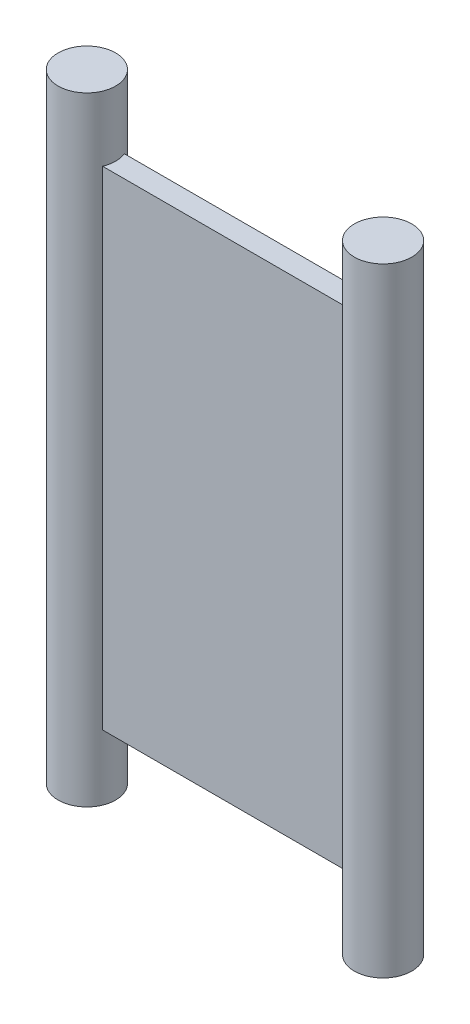
SolidWorks part; units mm, degrees
ref_plane "Front Plane" through (0, 0, 0) normal (0, 0, 1) x (1, 0, 0)
ref_plane "Top Plane" through (0, 0, 0) normal (0, 1, 0) x (1, 0, 0)
ref_plane "Right Plane" through (0, 0, 0) normal (1, 0, 0) x (0, 0, -1)
sketch "Sketch1" plane through (0, 0, 0) normal (0, 1, 0) x (1, 0, 0)
  line L1 (6.826, 0.5) -> (-6.826, 0.5)
  line L2 (6.826, 0.5) -> (6.826, -0.5)
  line L3 (6.826, -0.5) -> (-6.826, -0.5)
  line L4 (-6.826, 0.5) -> (-6.826, -0.5)
  line L5 (6.826, 0.5) -> (-6.826, -0.5) construction
  line L6 (6.826, -0.5) -> (-6.826, 0.5) construction
  point P0 (0, 0)
  dimension "D1" = 13.652
  dimension "D3" = 1
extrude "Boss-Extrude1" add sketch "Sketch1" along normal blind 22.5
ref_plane "Plane1" through (0, 11.25, 0) normal (0, 1, 0) x (1, 0, 0)
sketch "Sketch2" plane through (0, 11.25, 0) normal (0, 1, 0) x (1, 0, 0)
  line L0 (6.826, -0.5) -> (6.826, 0.5) construction
  line L1 (-6.826, 0.5) -> (-6.826, -0.5) construction
  line L2 (6.826, -0.5) -> (6.826, 0.5) construction
  line L3 (-6.826, 0.5) -> (-6.826, -0.5) construction
  circle A0 centre (-6.826, 0) radius 1.325
  circle A1 centre (6.826, 0) radius 1.325
  dimension "D1" = 2.65
extrude "Boss-Extrude2" add sketch "Sketch2" along normal mid plane 28.5
